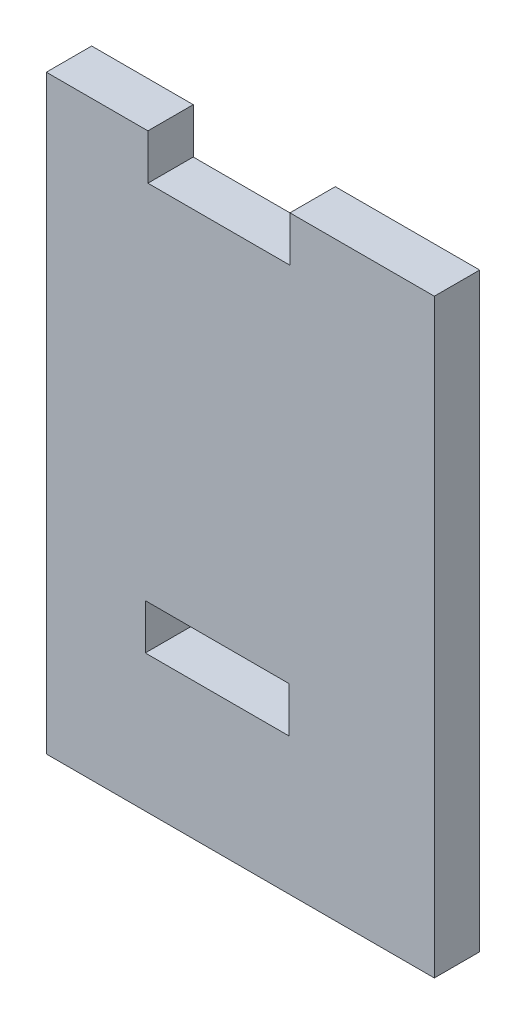
SolidWorks part; units mm, degrees
material "Beech"
ref_plane "Front" through (0, 0, 0) normal (0, 0, 1) x (1, 0, 0)
ref_plane "Top" through (0, 0, 0) normal (0, 1, 0) x (1, 0, 0)
ref_plane "Right" through (0, 0, 0) normal (1, 0, 0) x (0, 0, -1)
sketch "Sketch1" plane through (0, 0, 0) normal (0, 0, 1) x (1, 0, 0)
  line L0 (-10.695, 16.275) -> (-5.095, 16.275)
  line L1 (-10.695, -16.275) -> (10.695, -16.275)
  line L2 (-10.695, -16.275) -> (-10.695, 16.275)
  line L3 (-10.695, 16.275) -> (10.695, 16.275) construction
  line L4 (10.695, -16.275) -> (10.695, 16.275)
  line L5 (-10.695, -16.275) -> (10.695, 16.275) construction
  line L6 (-10.695, 16.275) -> (10.695, -16.275) construction
  line L7 (-5.095, 16.275) -> (-5.095, 13.775)
  line L8 (-5.095, 13.775) -> (2.735, 13.775)
  line L9 (2.735, 13.775) -> (2.735, 16.275)
  line L10 (2.735, 16.275) -> (10.695, 16.275)
  line L16 (-5.24, -8.725) -> (2.69, -8.725)
  line L17 (-5.24, -8.725) -> (-5.24, -6.225)
  line L18 (-5.24, -6.225) -> (2.69, -6.225)
  line L19 (2.69, -8.725) -> (2.69, -6.225)
  line L20 (-5.24, -8.725) -> (2.69, -6.225) construction
  line L21 (-5.24, -6.225) -> (2.69, -8.725) construction
  point P0 (0, 0)
  point P6 (0, 0)
  point P11 (-1.275, -7.475)
  point P16 (0, 0)
  dimension "D1" = 32.55
  dimension "D2" = 21.39
  dimension "D3" = 5
  dimension "D4" = 7.96
  dimension "D5" = 22.5
  dimension "D6" = 5.6
  dimension "D7" = 9.42
  dimension "D8" = 7.93
extrude "Boss-Extrude1" add sketch "Sketch1" along normal blind 2.5
